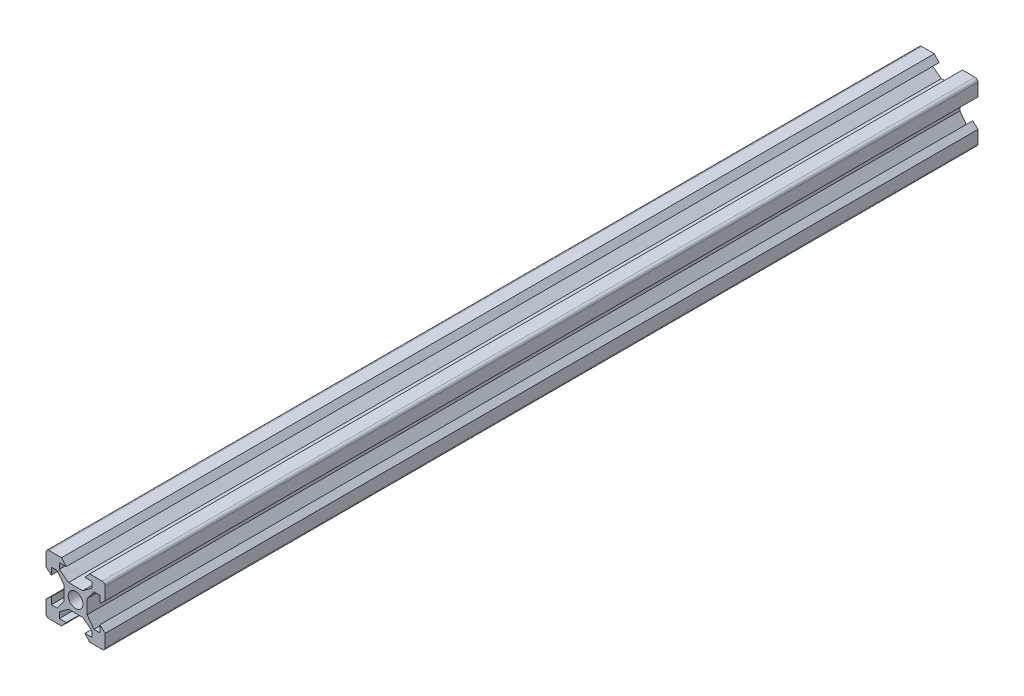
SolidWorks part; units mm, degrees
ref_plane "Front Plane" through (0, 0, 0) normal (0, 0, 1) x (1, 0, 0)
ref_plane "Top Plane" through (0, 0, 0) normal (0, 1, 0) x (1, 0, 0)
ref_plane "Right Plane" through (0, 0, 0) normal (1, 0, 0) x (0, 0, -1)
sketch "Sketch1" plane through (0, 0, 0) normal (0, 0, 1) x (1, 0, 0)
  line L0 (-5.5, 8.2) -> (-3.15, 8.2)
  line L5 (-10, -10) -> (10, 10) construction
  line L6 (-10, 10) -> (10, -10) construction
  line L7 (-9, 10) -> (-4.75, 10)
  line L8 (4.75, 10) -> (9, 10)
  line L9 (-4.75, 10) -> (-3.15, 8.2)
  line L10 (4.75, 10) -> (3.15, 8.2)
  line L11 (3.15, 8.2) -> (5.5, 8.2)
  line L12 (-5.5, 8.2) -> (-5.5, 6.2)
  line L13 (5.5, 8.2) -> (5.5, 6.2)
  line L14 (2.3879, 3.9) -> (-2.3879, 3.9)
  line L15 (-5.5, 6.2) -> (-2.3879, 3.9)
  line L16 (2.3879, 3.9) -> (5.5, 6.2)
  line L17 (10, 9) -> (10, 4.75)
  line L18 (10, 4.75) -> (8.2, 3.15)
  line L19 (10, -4.75) -> (8.2, -3.15)
  line L20 (8.2, -3.15) -> (8.2, -5.5)
  line L21 (8.2, 5.5) -> (8.2, 3.15)
  line L22 (8.2, 5.5) -> (6.2, 5.5)
  line L23 (6.2, 5.5) -> (3.9, 2.3879)
  line L24 (3.9, -2.3879) -> (3.9, 2.3879)
  line L25 (3.9, -2.3879) -> (6.2, -5.5)
  line L26 (8.2, -5.5) -> (6.2, -5.5)
  line L27 (10, -4.75) -> (10, -9)
  line L28 (9, -10) -> (4.75, -10)
  line L29 (4.75, -10) -> (3.15, -8.2)
  line L30 (-4.75, -10) -> (-3.15, -8.2)
  line L31 (-3.15, -8.2) -> (-5.5, -8.2)
  line L32 (5.5, -8.2) -> (3.15, -8.2)
  line L33 (5.5, -8.2) -> (5.5, -6.2)
  line L34 (5.5, -6.2) -> (2.3879, -3.9)
  line L35 (-2.3879, -3.9) -> (2.3879, -3.9)
  line L36 (-2.3879, -3.9) -> (-5.5, -6.2)
  line L37 (-5.5, -8.2) -> (-5.5, -6.2)
  line L38 (-4.75, -10) -> (-9, -10)
  line L39 (-10, -9) -> (-10, -4.75)
  line L40 (-10, -4.75) -> (-8.2, -3.15)
  line L41 (-10, 4.75) -> (-8.2, 3.15)
  line L42 (-8.2, 3.15) -> (-8.2, 5.5)
  line L43 (-8.2, -5.5) -> (-8.2, -3.15)
  line L44 (-8.2, -5.5) -> (-6.2, -5.5)
  line L45 (-6.2, -5.5) -> (-3.9, -2.3879)
  line L46 (-3.9, 2.3879) -> (-3.9, -2.3879)
  line L47 (-3.9, 2.3879) -> (-6.2, 5.5)
  line L48 (-8.2, 5.5) -> (-6.2, 5.5)
  line L49 (-10, 4.75) -> (-10, 9)
  arc A0 (9, 10) -> (10, 9) centre (9, 9) cw
  arc A1 (9, -10) -> (10, -9) centre (9, -9) ccw
  arc A2 (-9, -10) -> (-10, -9) centre (-9, -9) cw
  arc A3 (-10, 9) -> (-9, 10) centre (-9, 9) cw
  circle A4 centre (0, 0) radius 2.5
  point P0 (0, 0)
  point P21 (0, 10)
  point P24 (0, 8.2)
  point P27 (0, 8.2)
  point P32 (0, 3.9)
  point P71 (0, 0)
  dimension "D3" = 1
  dimension "D12" = 5
  dimension "D1" = 20
  dimension "D2" = 20
  dimension "D4" = 9.5
  dimension "D5" = 6.3
  dimension "D6" = 0
  dimension "D7" = 10
  dimension "D8" = 6.1
  dimension "D9" = 11
  dimension "D10" = 2
  dimension "D11" = 4
extrude "Boss-Extrude1" add sketch "Sketch1" along normal blind 295
